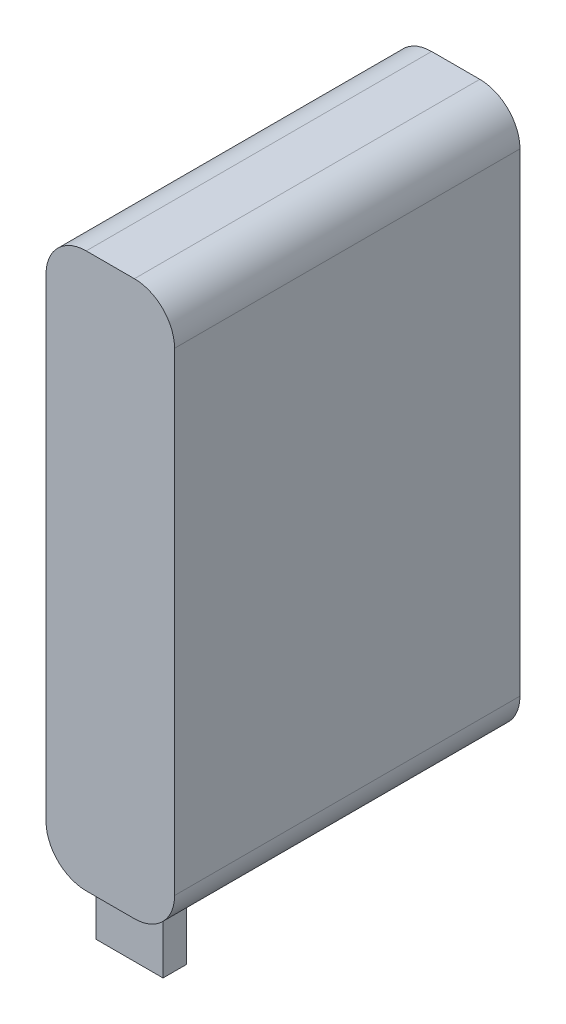
SolidWorks part; units mm, degrees
ref_plane "Plano frontal" through (0, 0, 0) normal (0, 0, 1) x (1, 0, 0)
ref_plane "Plano superior" through (0, 0, 0) normal (0, 1, 0) x (1, 0, 0)
ref_plane "Plano direito" through (0, 0, 0) normal (1, 0, 0) x (0, 0, -1)
sketch "Esboço4" plane through (0, 0, 0) normal (0, 0, 1) x (1, 0, 0)
  line L1 (-3, 34.5) -> (3, 34.5)
  line L2 (-8, 29.5) -> (-8, -29.5)
  line L3 (-3, -34.5) -> (3, -34.5)
  line L4 (8, 29.5) -> (8, -29.5)
  line L5 (-8, 34.5) -> (8, -34.5) construction
  line L6 (-8, -34.5) -> (8, 34.5) construction
  arc A0 (-8, -29.5) -> (-3, -34.5) centre (-3, -29.5) ccw
  arc A1 (3, -34.5) -> (8, -29.5) centre (3, -29.5) ccw
  arc A2 (3, 34.5) -> (8, 29.5) centre (3, 29.5) cw
  arc A3 (-3, 34.5) -> (-8, 29.5) centre (-3, 29.5) ccw
  point P0 (0, 0)
  dimension "D1" = 5
extrude "Ressalto-extrusão4" add sketch "Esboço4" along normal blind 43
sketch "Esboço5" plane through (0, -34.5, 0) normal (0, -1, 0) x (1, 0, 0)
  line L1 (-4.1755, 40.6087) -> (4.1755, 40.6087)
  line L2 (-4.1755, 40.6087) -> (-4.1755, 37.709)
  line L3 (-4.1755, 37.709) -> (4.1755, 37.709)
  line L4 (4.1755, 40.6087) -> (4.1755, 37.709)
  line L5 (-4.1755, 40.6087) -> (4.1755, 37.709) construction
  line L6 (-4.1755, 37.709) -> (4.1755, 40.6087) construction
  point P0 (0, 39.1589)
extrude "Ressalto-extrusão5" add sketch "Esboço5" along normal blind 7 and the other way blind 10
